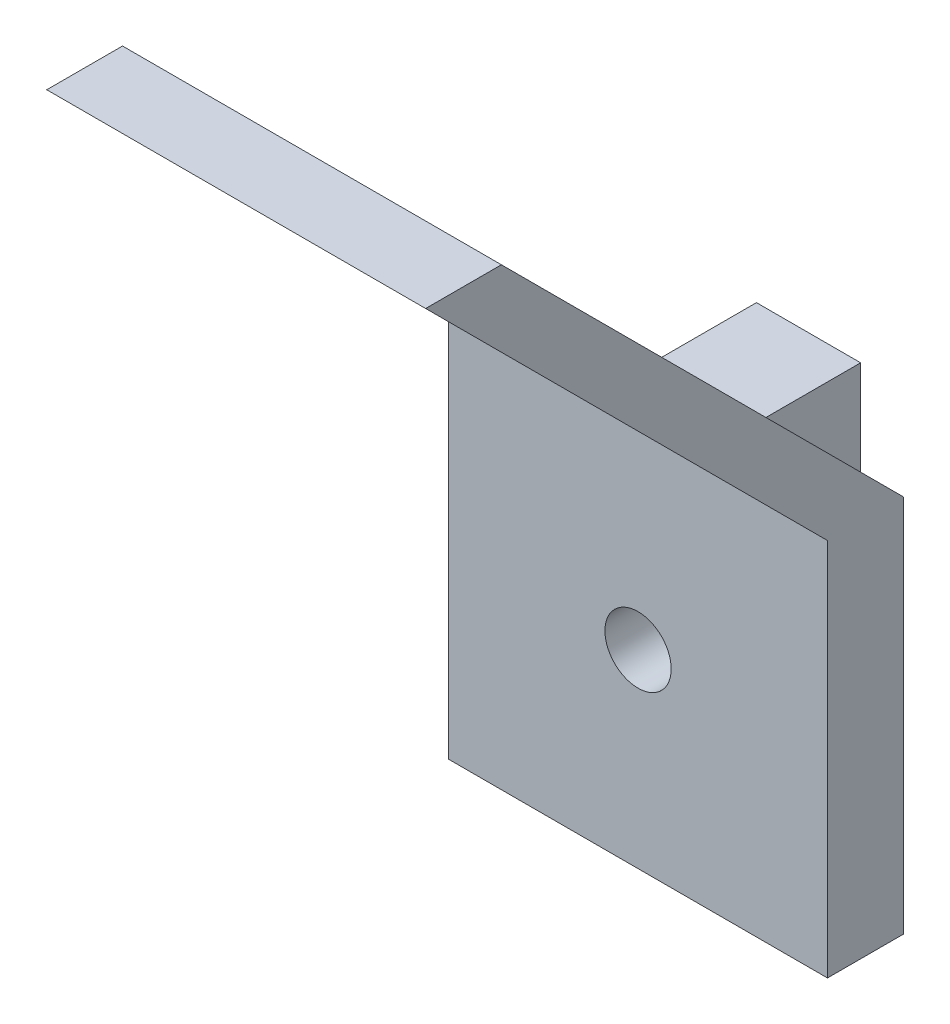
SolidWorks part; units mm, degrees
ref_plane "Front Plane" through (0, 0, 0) normal (0, 0, 1) x (1, 0, 0)
ref_plane "Top Plane" through (0, 0, 0) normal (0, 1, 0) x (1, 0, 0)
ref_plane "Right Plane" through (0, 0, 0) normal (1, 0, 0) x (0, 0, -1)
sketch "Sketch5" plane through (0, 0, 0) normal (1, 0, 0) x (0, 0, -1)
  line L0 (0, 0) -> (0, 20)
  line L1 (0, 20) -> (-21.2132, 41.2132)
  line L2 (-21.2132, 41.2132) -> (-25.2132, 41.2132)
  line L3 (-25.2132, 41.2132) -> (-4, 20)
  line L4 (-4, 20) -> (-4, 0)
  line L5 (-4, 0) -> (0, 0)
  dimension "D1" = 20
  dimension "D2" = 135
  dimension "D3" = 30
  dimension "D4" = 4
  dimension "D5" = 4
extrude "Boss-Extrude4" add sketch "Sketch5" along normal blind 20
sketch "Sketch6" plane through (0, 0, 4) normal (0, 0, 1) x (1, 0, 0)
  line L0 (10, 20) -> (10, 0) construction
  line L1 (20, 20) -> (0, 20) construction
  line L2 (20, 0) -> (0, 0) construction
  circle A0 centre (10, 10) radius 1.75
  dimension "D1" = 3.5
sketch "Sketch7" plane through (0, 8, -8) normal (0, -0.7071, 0.7071) x (1, 0, 0)
  line L0 (10, 46.9706) -> (10, 16.9706) construction
  line L1 (20, 46.9706) -> (0, 46.9706) construction
  circle A0 centre (10, 31.9706) radius 3.3782
  dimension "D1" = 6.7564
extrude "Cut-Extrude3" cut sketch "Sketch6" against normal through all
extrude "Cut-Extrude4" cut sketch "Sketch7" against normal through all
sketch "Sketch8" plane through (0, 0, 0) normal (0, 0, -1) x (-1, 0, 0)
  line L0 (-20, 20) -> (0, 20) construction
  line L1 (-7.25, 15) -> (-12.75, 15)
  line L2 (-7.25, 15) -> (-7.25, 20)
  line L3 (-7.25, 20) -> (-12.75, 20)
  line L4 (-12.75, 15) -> (-12.75, 20)
  line L5 (-7.25, 15) -> (-12.75, 20) construction
  line L6 (-7.25, 20) -> (-12.75, 15) construction
  line L7 (-7.25, 0) -> (-12.75, 0)
  line L8 (-7.25, 0) -> (-7.25, 5)
  line L9 (-7.25, 5) -> (-12.75, 5)
  line L10 (-12.75, 0) -> (-12.75, 5)
  line L11 (-7.25, 0) -> (-12.75, 5) construction
  line L12 (-7.25, 5) -> (-12.75, 0) construction
  line L13 (-20, 0) -> (0, 0) construction
  point P0 (-10, 17.5)
  point P7 (-10, 20)
  point P8 (0, 0)
  point P9 (-10, 2.5)
  point P14 (-10, 0)
  dimension "D1" = 5.5
  dimension "D2" = 5
  dimension "D3" = 5.5
  dimension "D4" = 5
extrude "Boss-Extrude5" add sketch "Sketch8" along normal blind 5
